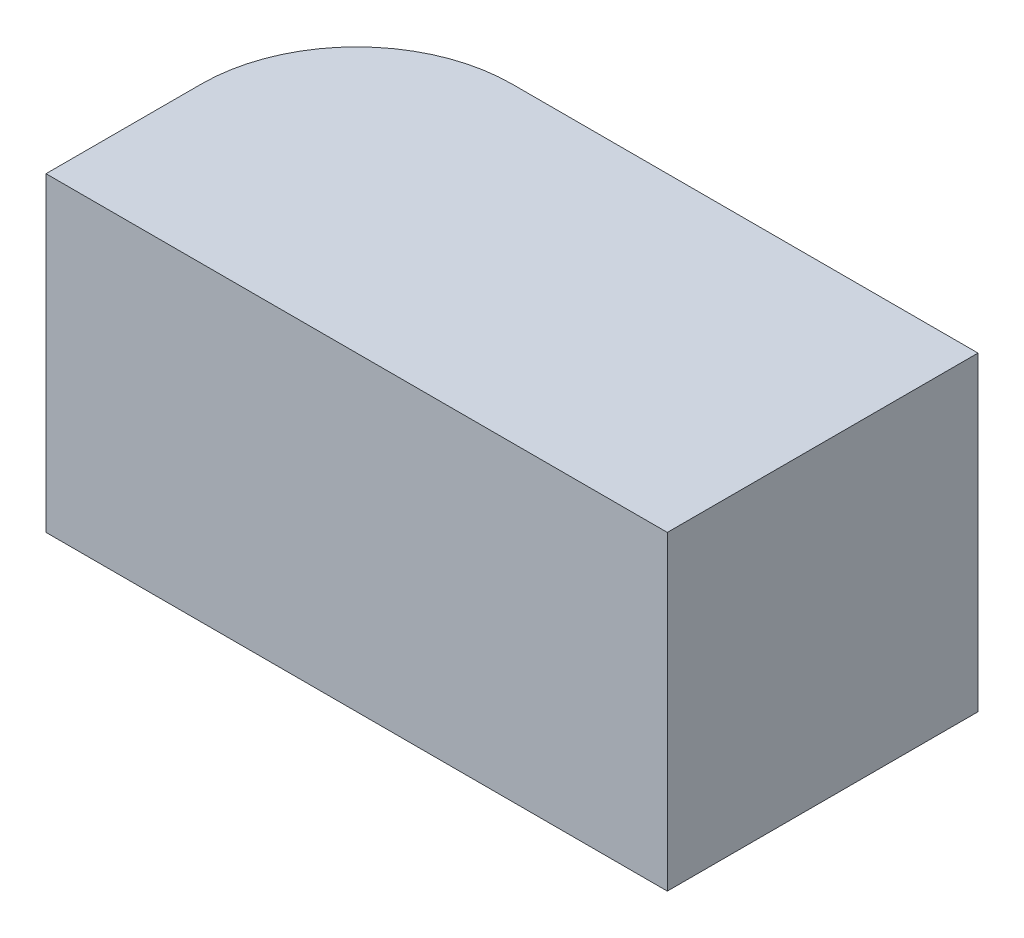
SolidWorks part; units mm, degrees
ref_plane "Přední rovina" through (0, 0, 0) normal (0, 0, 1) x (1, 0, 0)
ref_plane "Horní rovina" through (0, 0, 0) normal (0, 1, 0) x (1, 0, 0)
ref_plane "Pravá rovina" through (0, 0, 0) normal (1, 0, 0) x (0, 0, -1)
sketch "Sketch1" plane through (0, 0, 0) normal (0, 1, 0) x (1, 0, 0)
  line L0 (0, 0) -> (30, 0)
  line L1 (-10, -20) -> (30, -20)
  line L2 (-10, -20) -> (-10, -10)
  line L4 (30, -20) -> (30, 0)
  arc A0 (-10, -10) -> (0, 0) centre (0, -10) cw
  point P1 (2.6369, -10.8234)
  dimension "D1" = 10
  dimension "D2" = 40
  dimension "D3" = 20
extrude "Boss-Extrude1" add sketch "Sketch1" along normal blind 20
equation "\"R\"= 10'Radius"
equation "\"H\"= 20'Extrude height"
equation "\"D1@Boss-Extrude1\"=\"H\""
equation "\"D2@Sketch1\"=\"R\"*4"
equation "\"D3@Sketch1\"=\"R\"*2mm"
equation "\"D1@Sketch1\"=\"R\""
